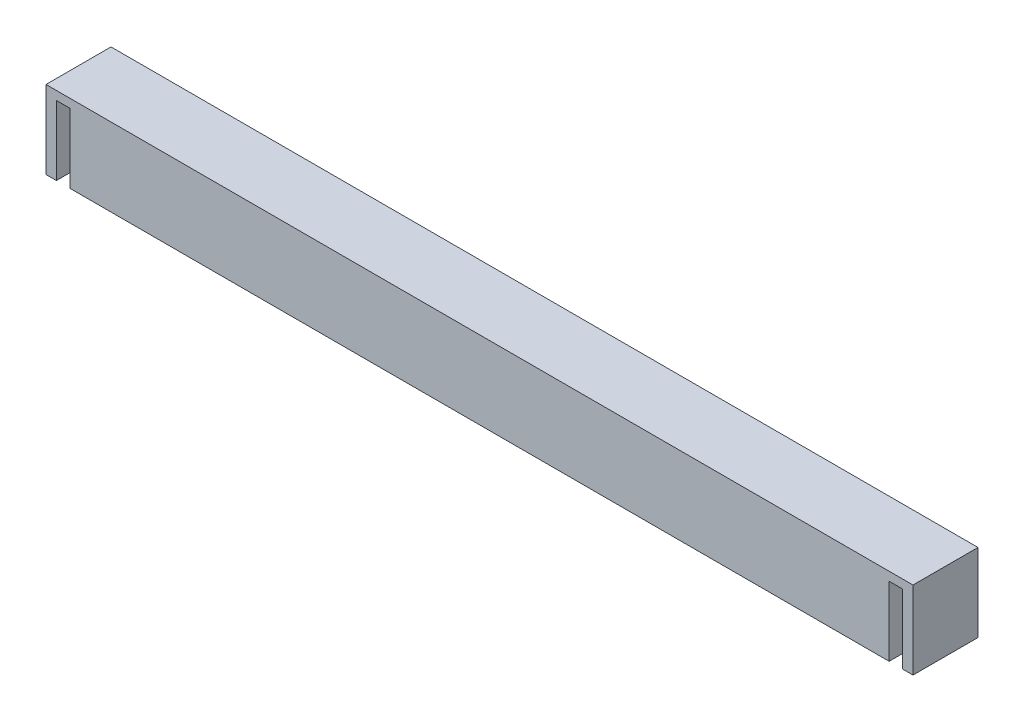
SolidWorks part; units mm, degrees
ref_plane "Front Plane" through (0, 0, 0) normal (0, 0, 1) x (1, 0, 0)
ref_plane "Top Plane" through (0, 0, 0) normal (0, 1, 0) x (1, 0, 0)
ref_plane "Right Plane" through (0, 0, 0) normal (1, 0, 0) x (0, 0, -1)
sketch "Sketch1" plane through (0, 0, 0) normal (0, 1, 0) x (1, 0, 0)
  line L1 (-100, 7.5) -> (100, 7.5)
  line L2 (-100, 7.5) -> (-100, -7.5)
  line L3 (-100, -7.5) -> (100, -7.5)
  line L4 (100, 7.5) -> (100, -7.5)
  line L5 (-100, 7.5) -> (100, -7.5) construction
  line L6 (-100, -7.5) -> (100, 7.5) construction
  point P0 (0, 0)
  dimension "D1" = 15
  dimension "D2" = 200
extrude "Front Top Beam" add sketch "Sketch1" along normal blind 18
sketch "Sketch2" plane through (0, 0, 0) normal (0, -1, 0) x (1, 0, 0)
  line L0 (-100, 7.5) -> (100, 7.5) construction
  line L1 (-97.6, 7.5) -> (-94.5, 7.5)
  line L2 (-97.6, 7.5) -> (-97.6, -7.5)
  line L3 (-97.6, -7.5) -> (-94.5, -7.5)
  line L4 (-94.5, 7.5) -> (-94.5, -7.5)
  line L5 (100, -7.5) -> (-100, -7.5) construction
  line L6 (-100, -7.5) -> (-100, 7.5) construction
  line L7 (94.5, 7.5) -> (97.6, 7.5)
  line L8 (94.5, 7.5) -> (94.5, -7.5)
  line L9 (94.5, -7.5) -> (97.6, -7.5)
  line L10 (97.6, 7.5) -> (97.6, -7.5)
  line L12 (100, 7.5) -> (100, -7.5) construction
  dimension "D1" = 5.5
  dimension "D2" = 2.4
  dimension "D3" = 2.4
  dimension "D4" = 5.5
extrude "Front Top Grooves" cut sketch "Sketch2" against normal blind 16
sketch "Sketch3" plane through (100, 0, 0) normal (1, 0, 0) x (0, 0, -1)
  line L0 (-7.5, 18) -> (7.5, 18) construction
  line L1 (2.5, 0) -> (-2.5, 0)
  line L2 (2.5, 0) -> (2.5, 18)
  line L3 (2.5, 18) -> (-2.5, 18)
  line L4 (-2.5, 0) -> (-2.5, 18)
  line L5 (2.5, 0) -> (-2.5, 18) construction
  line L6 (2.5, 18) -> (-2.5, 0) construction
  line L7 (-7.5, 0) -> (7.5, 0) construction
  point P0 (0, 9)
  dimension "D1" = 5
extrude "Front Top Rib" add sketch "Sketch3" against normal through all
